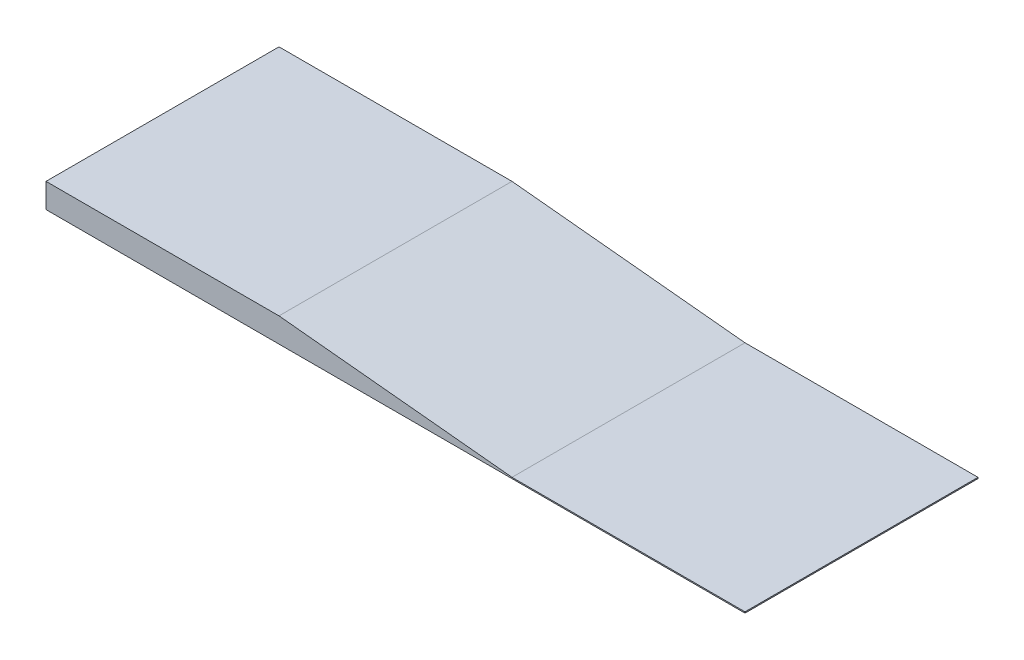
SolidWorks part; units mm, degrees
ref_plane "前视基准面" through (0, 0, 0) normal (0, 0, 1) x (1, 0, 0)
ref_plane "上视基准面" through (0, 0, 0) normal (0, 1, 0) x (1, 0, 0)
ref_plane "右视基准面" through (0, 0, 0) normal (1, 0, 0) x (0, 0, -1)
sketch "草图1" plane through (0, 0, 0) normal (0, 0, 1) x (1, 0, 0)
  line L0 (0, 0) -> (2000, -200)
  line L1 (2000, -200) -> (4000, -200)
  line L2 (4000, -200) -> (4000, -210)
  line L3 (4000, -210) -> (0, -210)
  line L4 (0, -210) -> (0, -200) construction
  line L5 (2000, -200) -> (0, -200) construction
  line L6 (0, -200) -> (0, 0) construction
  line L7 (0, -210) -> (-2000, -210)
  line L8 (0, -200) -> (0, 0) construction
  line L9 (0, 0) -> (-2000, 0)
  line L10 (-2000, -210) -> (-2000, 0)
  line L11 (0, -210) -> (0, -200) construction
  dimension "D1" = 200
  dimension "D2" = 2000
  dimension "D3" = 2000
  dimension "D4" = 10
  dimension "D5" = 2000
extrude "凸台-拉伸1" add sketch "草图1" along normal blind 2000
